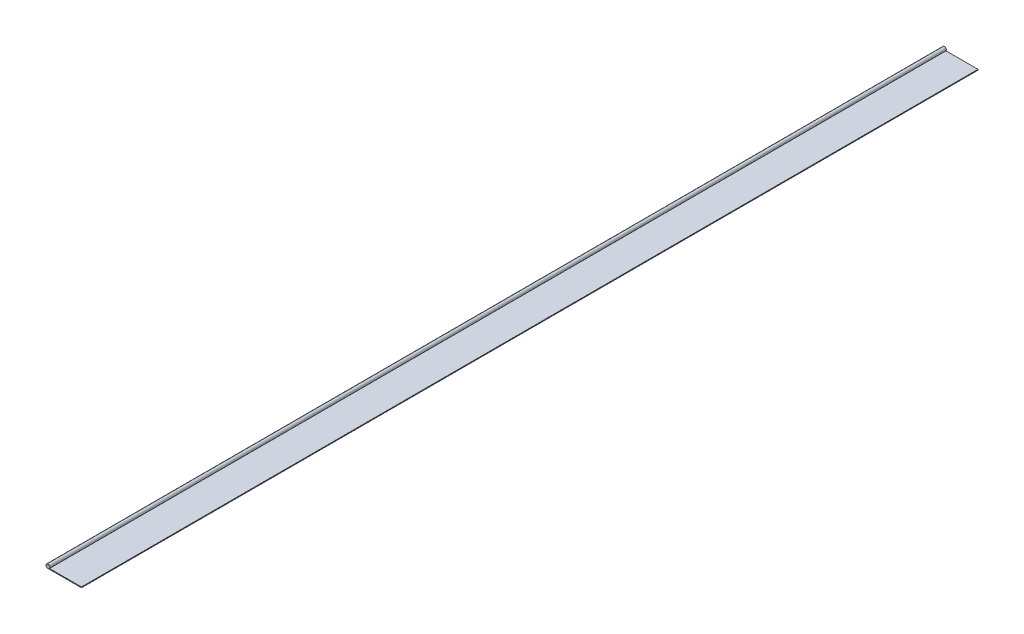
SolidWorks part; units mm, degrees
ref_plane "Front Plane" through (0, 0, 0) normal (0, 0, 1) x (1, 0, 0)
ref_plane "Top Plane" through (0, 0, 0) normal (0, 1, 0) x (1, 0, 0)
ref_plane "Right Plane" through (0, 0, 0) normal (1, 0, 0) x (0, 0, -1)
sketch "Sketch1" plane through (0, 0, 0) normal (0, 0, 1) x (1, 0, 0)
  line L0 (0, -1.5) -> (26.2, -1.5)
  line L4 (26.9325, 0.45) -> (26.9325, -0.45)
  line L5 (26.2, -1.5) -> (26.2, -0.9)
  line L6 (26.2, -0.9) -> (1.2, -0.9)
  arc A0 (1.2, -0.9) -> (0, -1.5) centre (0, 0) ccw
  point P1 (26.9325, 0)
  point P13 (1.9487, 0.5495)
  dimension "D1" = 3
  dimension "D2" = 25
  dimension "D3" = 0.9
  dimension "D4" = 0.6
extrude "Boss-Extrude1" add sketch "Sketch1" along normal blind 700 contours L6 A0 L0 L5
